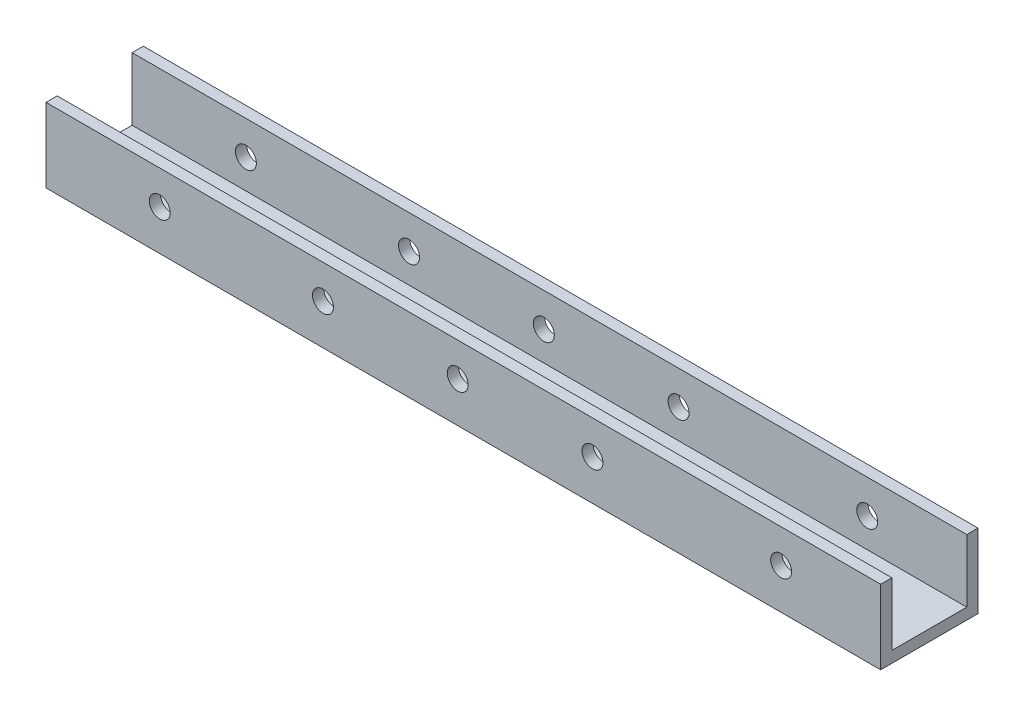
SolidWorks part; units mm, degrees
ref_plane "Plan de face" through (0, 0, 0) normal (0, 0, 1) x (1, 0, 0)
ref_plane "Plan de dessus" through (0, 0, 0) normal (0, 1, 0) x (1, 0, 0)
ref_plane "Plan de droite" through (0, 0, 0) normal (1, 0, 0) x (0, 0, -1)
sketch "Esquisse1" plane through (0, 0, 0) normal (0, 1, 0) x (1, 0, 0)
  line L0 (0, 0) -> (0, 13)
  line L1 (0, 13) -> (111.5, 13)
  line L2 (111.5, 13) -> (111.5, 0)
  line L3 (111.5, 0) -> (0, 0)
  dimension "D1" = 111.5
  dimension "D2" = 13
extrude "Boss.-Extru.1" add sketch "Esquisse1" along normal blind 1.5
sketch "Esquisse2" plane through (0, 1.5, 0) normal (0, 1, 0) x (1, 0, 0)
  line L0 (0, 13) -> (0, 11.5)
  line L1 (0, 13) -> (0, 0) construction
  line L2 (0, 11.5) -> (111.5, 11.5)
  line L3 (111.5, 0) -> (111.5, 13) construction
  line L4 (111.5, 11.5) -> (111.5, 13)
  line L5 (111.5, 13) -> (0, 13)
  line L6 (0, 6.5) -> (111.5, 6.5) construction
  line L7 (111.5, 0) -> (0, 0)
  line L8 (111.5, 1.5) -> (111.5, 0)
  line L9 (0, 1.5) -> (111.5, 1.5)
  line L10 (0, 0) -> (0, 1.5)
  dimension "D1" = 1.5
extrude "Boss.-Extru.2" add sketch "Esquisse2" along normal blind 8.4
sketch "Esquisse4" plane through (0, 0, 0) normal (0, 0, 1) x (1, 0, 0)
  circle A0 centre (37, 5.4) radius 1.4
  circle A1 centre (55, 5.4) radius 1.4
  circle A2 centre (73, 5.4) radius 1.4
  circle A3 centre (15.2003, 5.4) radius 1.4
  circle A4 centre (98.2003, 5.4) radius 1.4
  dimension "D2" = 2.8
  dimension "D6" = 2.8
  dimension "D1" = 4.5
  dimension "D4" = 37
  dimension "D5" = 18
  dimension "D3" = 3
  dimension "D7" = 2
extrude "Enlèv. mat.-Extru.1" cut sketch "Esquisse4" against normal blind 20
